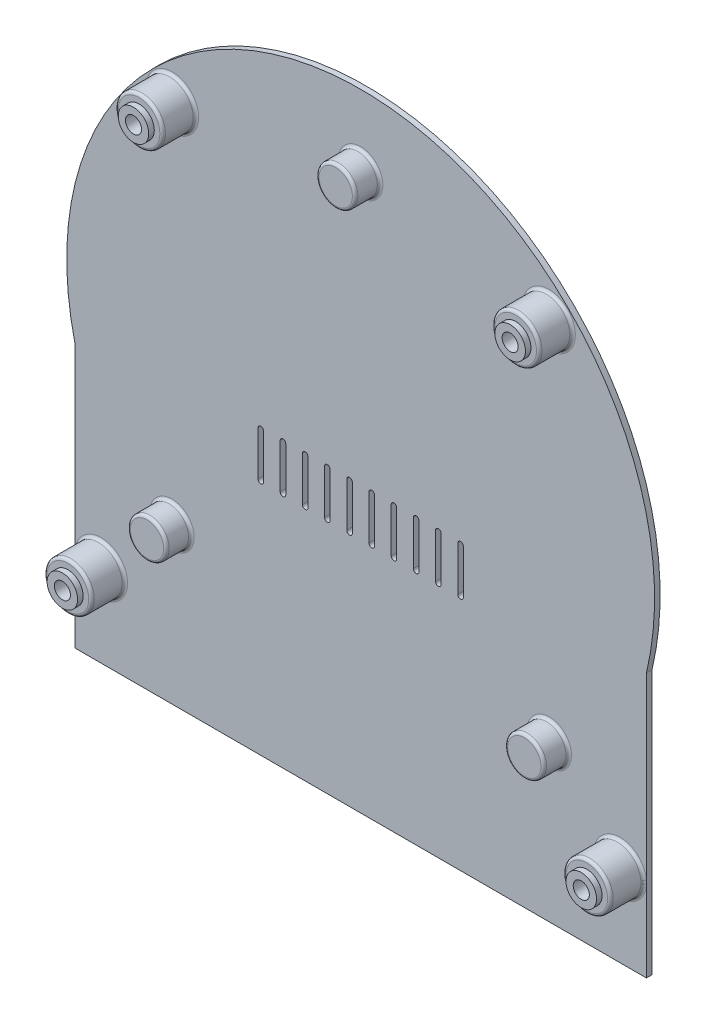
SolidWorks part; units mm, degrees
ref_plane "Plan de face" through (0, 0, 0) normal (0, 0, 1) x (1, 0, 0)
ref_plane "Plan de dessus" through (0, 0, 0) normal (0, 1, 0) x (1, 0, 0)
ref_plane "Plan de droite" through (0, 0, 0) normal (1, 0, 0) x (0, 0, -1)
sketch "Esquisse2" plane through (0, 0, 0) normal (0, 0, 1) x (1, 0, 0)
  line L0 (-51.5, -12.3924) -> (-51.5, -60)
  line L1 (-51.5, -60) -> (51.5, -60)
  line L2 (0, 0) -> (0, -108.8898) construction
  line L3 (51.5, -12.3924) -> (51.5, -60)
  arc A0 (51.5, -12.3924) -> (-51.5, -12.3924) centre (0, 0) ccw
  point P8 (0, -60)
  dimension "D1" = 105.94
  dimension "D2" = 51.5
  dimension "D4" = 60
extrude "Boss.-Extru.1" add sketch "Esquisse2" along normal blind 1
sketch "Esquisse3" plane through (0, 0, 1) normal (0, 0, 1) x (1, 0, 0)
  line L0 (0, 0) -> (-63.7935, 63.7935) construction
  line L1 (0, 0) -> (-75.5763, -72.9832) construction
  line L2 (0, 0) -> (0, 81.6107) construction
  circle A0 centre (0, 0) radius 48 construction
  circle A1 centre (0, 0) radius 65 construction
  circle A2 centre (-33.9411, 33.9411) radius 4.25
  circle A3 centre (-46.7571, -45.1528) radius 4.25
  dimension "D1" = 130
  dimension "D2" = 96
  dimension "D5" = 8.5
  dimension "D6" = 8.5
  dimension "D3" = 45
  dimension "D4" = 46
extrude "Boss.-Extru.2" add sketch "Esquisse3" along normal blind 6
sketch "Esquisse4" plane through (0, 0, 7) normal (0, 0, 1) x (1, 0, 0)
  circle A0 centre (-33.9411, 33.9411) radius 2.75
  circle A1 centre (-46.7571, -45.1528) radius 2.75
  dimension "D1" = 5.5
  dimension "D2" = 5.5
extrude "Boss.-Extru.3" add sketch "Esquisse4" along normal blind 1
hole_wizard "Chambrage pour vis à tête ronde bombée M2.52" positions "Esquisse7" profile "Esquisse6" counterbore size "M2.5" standard "ISO" end condition through all
sketch "Esquisse7" plane through (0, 0, 0) normal (0, 0, -1) x (-1, 0, 0)
  point P4 (33.9411, 33.9411)
  point P7 (46.7571, -45.1528)
sketch "Esquisse6" plane through (-33.9411, 33.9411, 0) normal (1, 0, 0) x (0, 1, 0)
  line L0 (0, 0) -> (0, 8)
  line L1 (0, 8) -> (1.45, 8)
  line L3 (1.45, 8) -> (1.45, 5.1)
  line L4 (1.45, 5.1) -> (3, 5.1)
  line L5 (3, 5.1) -> (3, 0)
  line L7 (3, 0) -> (0, 0)
  line L11 (0, -6.35) -> (0, 107.95) construction
  dimension "Diamètre du perçage jusqu'au prochain" = 2.9
  dimension "Profondeur du perçage jusqu'au prochain" = 8
  dimension "Diamètre du chambrage" = 6
  dimension "Profondeur du chambrage" = 5.1
sketch "Esquisse8" plane through (0, 0, 1) normal (0, 0, 1) x (1, 0, 0)
  line L0 (0, 50.2722) -> (0, -88.1935) construction
  circle A0 centre (0, 40) radius 3.5
  circle A1 centre (-34, -32) radius 3.5
  circle A2 centre (34, -32) radius 3.5
  dimension "D5" = 7
  dimension "D6" = 7
  dimension "D7" = 7
  dimension "D1" = 72
  dimension "D2" = 40
  dimension "D3" = 34
  dimension "D4" = 34
extrude "Boss.-Extru.4" add sketch "Esquisse8" along normal blind 4.5
fillet "Congé1" radius 0.5 10 edges at (37.5, -32, 1) (37.5, -32, 5.5) (-30.5, -32, 1) (-30.5, -32, 5.5) (3.5, 40, 1) (3.5, 40, 5.5) (-42.5071, -45.1528, 1) (-42.5071, -45.1528, 7) (-29.6911, 33.9411, 1) (-29.6911, 33.9411, 7)
sketch "Esquisse9" plane through (0, 0, 0) normal (0, 0, -1) x (-1, 0, 0)
  arc B0 (-33.7509, -30.5208) -> (-34.2491, -30.5208) centre (-34, -30.5) ccw
  arc B1 (-34.5238, -30.5944) -> (-34.9553, -30.8436) centre (-34.75, -30.701) ccw
  arc B2 (-35.1564, -31.0447) -> (-35.4056, -31.4762) centre (-35.299, -31.25) ccw
  arc B3 (-35.4792, -31.7509) -> (-35.4792, -32.2491) centre (-35.5, -32) ccw
  arc B4 (-35.4056, -32.5238) -> (-35.1564, -32.9553) centre (-35.299, -32.75) ccw
  arc B5 (-34.9553, -33.1564) -> (-34.5238, -33.4056) centre (-34.75, -33.299) ccw
  arc B6 (-34.2491, -33.4792) -> (-33.7509, -33.4792) centre (-34, -33.5) ccw
  arc B7 (-33.4762, -33.4056) -> (-33.0447, -33.1564) centre (-33.25, -33.299) ccw
  arc B8 (-32.8436, -32.9553) -> (-32.5944, -32.5238) centre (-32.701, -32.75) ccw
  arc B9 (-32.5208, -32.2491) -> (-32.5208, -31.7509) centre (-32.5, -32) ccw
  arc B10 (-32.5944, -31.4762) -> (-32.8436, -31.0447) centre (-32.701, -31.25) ccw
  arc B11 (-33.0447, -30.8436) -> (-33.4762, -30.5944) centre (-33.25, -30.701) ccw
  arc B12 (-33.4762, -30.5944) -> (-33.7509, -30.5208) centre (-34, -32) ccw
  arc B13 (-34.2491, -30.5208) -> (-34.5238, -30.5944) centre (-34, -32) ccw
  arc B14 (-34.9553, -30.8436) -> (-35.1564, -31.0447) centre (-34, -32) ccw
  arc B15 (-35.4056, -31.4762) -> (-35.4792, -31.7509) centre (-34, -32) ccw
  arc B16 (-35.4792, -32.2491) -> (-35.4056, -32.5238) centre (-34, -32) ccw
  arc B17 (-35.1564, -32.9553) -> (-34.9553, -33.1564) centre (-34, -32) ccw
  arc B18 (-34.5238, -33.4056) -> (-34.2491, -33.4792) centre (-34, -32) ccw
  arc B19 (-33.7509, -33.4792) -> (-33.4762, -33.4056) centre (-34, -32) ccw
  arc B20 (-33.0447, -33.1564) -> (-32.8436, -32.9553) centre (-34, -32) ccw
  arc B21 (-32.5944, -32.5238) -> (-32.5208, -32.2491) centre (-34, -32) ccw
  arc B22 (-32.5208, -31.7509) -> (-32.5944, -31.4762) centre (-34, -32) ccw
  arc B23 (-32.8436, -31.0447) -> (-33.0447, -30.8436) centre (-34, -32) ccw
  arc B24 (34.2491, -30.5208) -> (33.7509, -30.5208) centre (34, -30.5) ccw
  arc B25 (33.4762, -30.5944) -> (33.0447, -30.8436) centre (33.25, -30.701) ccw
  arc B26 (32.8436, -31.0447) -> (32.5944, -31.4762) centre (32.701, -31.25) ccw
  arc B27 (32.5208, -31.7509) -> (32.5208, -32.2491) centre (32.5, -32) ccw
  arc B28 (32.5944, -32.5238) -> (32.8436, -32.9553) centre (32.701, -32.75) ccw
  arc B29 (33.0447, -33.1564) -> (33.4762, -33.4056) centre (33.25, -33.299) ccw
  arc B30 (33.7509, -33.4792) -> (34.2491, -33.4792) centre (34, -33.5) ccw
  arc B31 (34.5238, -33.4056) -> (34.9553, -33.1564) centre (34.75, -33.299) ccw
  arc B32 (35.1564, -32.9553) -> (35.4056, -32.5238) centre (35.299, -32.75) ccw
  arc B33 (35.4792, -32.2491) -> (35.4792, -31.7509) centre (35.5, -32) ccw
  arc B34 (35.4056, -31.4762) -> (35.1564, -31.0447) centre (35.299, -31.25) ccw
  arc B35 (34.9553, -30.8436) -> (34.5238, -30.5944) centre (34.75, -30.701) ccw
  arc B36 (34.5238, -30.5944) -> (34.2491, -30.5208) centre (34, -32) ccw
  arc B37 (33.7509, -30.5208) -> (33.4762, -30.5944) centre (34, -32) ccw
  arc B38 (33.0447, -30.8436) -> (32.8436, -31.0447) centre (34, -32) ccw
  arc B39 (32.5944, -31.4762) -> (32.5208, -31.7509) centre (34, -32) ccw
  arc B40 (32.5208, -32.2491) -> (32.5944, -32.5238) centre (34, -32) ccw
  arc B41 (32.8436, -32.9553) -> (33.0447, -33.1564) centre (34, -32) ccw
  arc B42 (33.4762, -33.4056) -> (33.7509, -33.4792) centre (34, -32) ccw
  arc B43 (34.2491, -33.4792) -> (34.5238, -33.4056) centre (34, -32) ccw
  arc B44 (34.9553, -33.1564) -> (35.1564, -32.9553) centre (34, -32) ccw
  arc B45 (35.4056, -32.5238) -> (35.4792, -32.2491) centre (34, -32) ccw
  arc B46 (35.4792, -31.7509) -> (35.4056, -31.4762) centre (34, -32) ccw
  arc B47 (35.1564, -31.0447) -> (34.9553, -30.8436) centre (34, -32) ccw
  arc B48 (0.2491, 41.4792) -> (-0.2491, 41.4792) centre (0, 41.5) ccw
  arc B49 (-0.5238, 41.4056) -> (-0.9553, 41.1564) centre (-0.75, 41.299) ccw
  arc B50 (-1.1564, 40.9553) -> (-1.4056, 40.5238) centre (-1.299, 40.75) ccw
  arc B51 (-1.4792, 40.2491) -> (-1.4792, 39.7509) centre (-1.5, 40) ccw
  arc B52 (-1.4056, 39.4762) -> (-1.1564, 39.0447) centre (-1.299, 39.25) ccw
  arc B53 (-0.9553, 38.8436) -> (-0.5238, 38.5944) centre (-0.75, 38.701) ccw
  arc B54 (-0.2491, 38.5208) -> (0.2491, 38.5208) centre (0, 38.5) ccw
  arc B55 (0.5238, 38.5944) -> (0.9553, 38.8436) centre (0.75, 38.701) ccw
  arc B56 (1.1564, 39.0447) -> (1.4056, 39.4762) centre (1.299, 39.25) ccw
  arc B57 (1.4792, 39.7509) -> (1.4792, 40.2491) centre (1.5, 40) ccw
  arc B58 (1.4056, 40.5238) -> (1.1564, 40.9553) centre (1.299, 40.75) ccw
  arc B59 (0.9553, 41.1564) -> (0.5238, 41.4056) centre (0.75, 41.299) ccw
  arc B60 (0.5238, 41.4056) -> (0.2491, 41.4792) centre (0, 40) ccw
  arc B61 (-0.2491, 41.4792) -> (-0.5238, 41.4056) centre (0, 40) ccw
  arc B62 (-0.9553, 41.1564) -> (-1.1564, 40.9553) centre (0, 40) ccw
  arc B63 (-1.4056, 40.5238) -> (-1.4792, 40.2491) centre (0, 40) ccw
  arc B64 (-1.4792, 39.7509) -> (-1.4056, 39.4762) centre (0, 40) ccw
  arc B65 (-1.1564, 39.0447) -> (-0.9553, 38.8436) centre (0, 40) ccw
  arc B66 (-0.5238, 38.5944) -> (-0.2491, 38.5208) centre (0, 40) ccw
  arc B67 (0.2491, 38.5208) -> (0.5238, 38.5944) centre (0, 40) ccw
  arc B68 (0.9553, 38.8436) -> (1.1564, 39.0447) centre (0, 40) ccw
  arc B69 (1.4056, 39.4762) -> (1.4792, 39.7509) centre (0, 40) ccw
  arc B70 (1.4792, 40.2491) -> (1.4056, 40.5238) centre (0, 40) ccw
  arc B71 (1.1564, 40.9553) -> (0.9553, 41.1564) centre (0, 40) ccw
sketch_block_instance "Bloc1-1"
sketch_block "Bloc1"
sketch_block_instance "Bloc1-2"
sketch_block_instance "Bloc1-3"
extrude "Enlèv. mat.-Extru.1" cut sketch "Esquisse9" against normal blind 5
sketch "Esquisse10" plane through (0, 0, 0) normal (0, 0, -1) x (-1, 0, 0)
  line L0 (0, 0) -> (0, -42.8863) construction
  line L1 (-2, -9.1163) -> (-2, -17.1163) construction
  line L2 (-1.5, -9.1163) -> (-1.5, -17.1163)
  line L3 (-2.5, -9.1163) -> (-2.5, -17.1163)
  line L4 (-6, -9.1163) -> (-6, -17.1163) construction
  line L5 (-5.5, -9.1163) -> (-5.5, -17.1163)
  line L6 (-6.5, -9.1163) -> (-6.5, -17.1163)
  line L7 (-10, -9.1163) -> (-10, -17.1163) construction
  line L8 (-9.5, -9.1163) -> (-9.5, -17.1163)
  line L9 (-10.5, -9.1163) -> (-10.5, -17.1163)
  line L10 (-14, -9.1163) -> (-14, -17.1163) construction
  line L11 (-13.5, -9.1163) -> (-13.5, -17.1163)
  line L12 (-14.5, -9.1163) -> (-14.5, -17.1163)
  line L13 (-18, -9.1163) -> (-18, -17.1163) construction
  line L14 (-17.5, -9.1163) -> (-17.5, -17.1163)
  line L15 (-18.5, -9.1163) -> (-18.5, -17.1163)
  arc A0 (-1.5, -9.1163) -> (-2.5, -9.1163) centre (-2, -9.1163) ccw
  arc A1 (-2.5, -17.1163) -> (-1.5, -17.1163) centre (-2, -17.1163) ccw
  arc A2 (-5.5, -9.1163) -> (-6.5, -9.1163) centre (-6, -9.1163) ccw
  arc A3 (-6.5, -17.1163) -> (-5.5, -17.1163) centre (-6, -17.1163) ccw
  arc A4 (-9.5, -9.1163) -> (-10.5, -9.1163) centre (-10, -9.1163) ccw
  arc A5 (-10.5, -17.1163) -> (-9.5, -17.1163) centre (-10, -17.1163) ccw
  arc A6 (-13.5, -9.1163) -> (-14.5, -9.1163) centre (-14, -9.1163) ccw
  arc A7 (-14.5, -17.1163) -> (-13.5, -17.1163) centre (-14, -17.1163) ccw
  arc A8 (-17.5, -9.1163) -> (-18.5, -9.1163) centre (-18, -9.1163) ccw
  arc A9 (-18.5, -17.1163) -> (-17.5, -17.1163) centre (-18, -17.1163) ccw
  point P5 (-2, -13.1163)
  point P13 (-6, -13.1163)
  point P20 (-10, -13.1163)
  point P27 (-14, -13.1163)
  point P34 (-18, -13.1163)
  dimension "D2" = 0.5
  dimension "D1" = 8
  dimension "D3" = 2
  dimension "D4" = 5
extrude "Enlèv. mat.-Extru.2" cut sketch "Esquisse10" against normal through all
mirror "Symétrie1" about plane through (0, 0, 0) normal (1, 0, 0) of "Boss.-Extru.2", "Boss.-Extru.3", "Chambrage pour vis à tête ronde bombée M2.52", "Congé1", "Enlèv. mat.-Extru.2"
